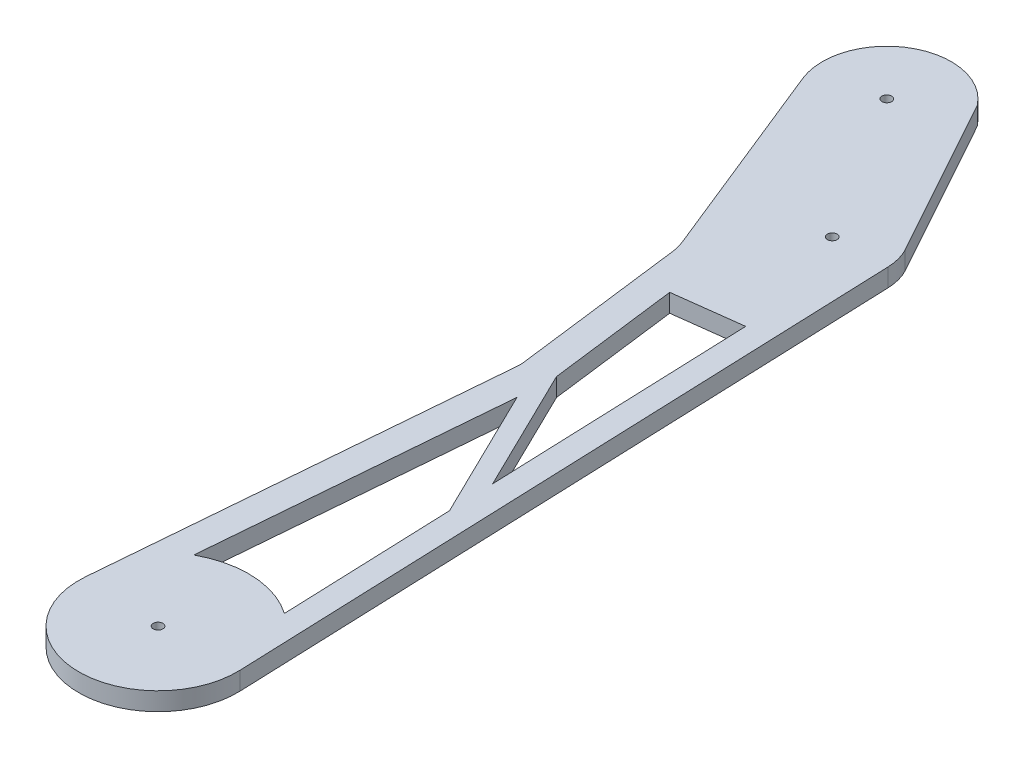
SolidWorks part; units mm, degrees
ref_plane "Front Plane" through (0, 0, 0) normal (0, 0, 1) x (1, 0, 0)
ref_plane "Top Plane" through (0, 0, 0) normal (0, 1, 0) x (1, 0, 0)
ref_plane "Right Plane" through (0, 0, 0) normal (1, 0, 0) x (0, 0, -1)
sketch "Sketch1" plane through (0, 0, 0) normal (0, 1, 0) x (1, 0, 0)
  line L0 (0, 0) -> (0, 63.6789) construction
  line L1 (0, 0) -> (0, 118.022) construction
  line L2 (-7.9677, 70.7448) -> (-13.823, 1.1632)
  line L3 (9.4394, 118.3762) -> (11.1381, 73.1106)
  line L4 (11.1381, 73.1106) -> (13.8621, 0.5202)
  line L5 (-7.2782, 150.7036) -> (8.3679, 122.4044)
  line L6 (-26.6184, 139.4994) -> (-12.3575, 104.1458)
  line L7 (-11.7436, 101.7851) -> (-7.9953, 72.0721)
  line L8 (-2.9552, 72.7079) -> (-5.8163, 95.3881)
  line L9 (-5.8163, 95.3881) -> (5.9914, 96.8777)
  line L10 (-2.9056, 70.3189) -> (-7.6525, 13.9088)
  line L11 (5.9914, 96.8777) -> (9.1397, 12.98)
  line L12 (-2.9552, 72.7079) -> (7.7186, 50.85)
  line L13 (-3.2608, 66.098) -> (8.0127, 43.0122)
  line L14 (8.0127, 43.0122) -> (7.7186, 50.85)
  line L15 (-3.2608, 66.098) -> (-2.9056, 70.3189)
  arc A0 (-13.823, 1.1632) -> (13.8621, 0.5202) centre (0, 0) ccw
  arc A1 (8.3679, 122.4044) -> (9.4394, 118.3762) centre (0, 118.022) cw
  arc A2 (-7.9677, 70.7448) -> (-7.9953, 72.0721) centre (-14.2953, 71.2773) ccw
  circle A3 centre (0, 118.022) radius 0.8509
  arc A4 (-26.6184, 139.4994) -> (-7.2782, 150.7036) centre (-16.1493, 143.7224) cw
  circle A5 centre (-16.1493, 143.7224) radius 0.8509
  arc A6 (-12.3575, 104.1458) -> (-11.7436, 101.7851) centre (-21.1521, 100.5983) cw
  circle A7 centre (0, 0) radius 0.8509
  arc A8 (9.1397, 12.98) -> (-7.6525, 13.9088) centre (0, 0) ccw
  arc A9 (-2.9552, 72.7079) -> (-2.9056, 70.3189) centre (-14.2953, 71.2773) cw
  arc A10 (-2.9056, 70.3189) -> (-2.9552, 72.7079) centre (-14.2953, 71.2773) ccw
  point P9 (0, 82.55)
  point P13 (0, 82.55)
  point P18 (0, 63.5)
  point P20 (0, 101.6)
  point P23 (11.1381, 73.1106)
  point P40 (0, 0)
  point P41 (0, 0)
  point P42 (0, 0)
  point P43 (-7.9677, 14.7019)
  point P44 (0, 0)
  point P45 (0, 0)
  point P46 (0, 0)
  dimension "D1" = 6.35
  dimension "D2" = 1.7018
  dimension "D11" = 1.7018
  dimension "D16" = 11.2887
  dimension "D18" = 9.4831
  dimension "D20" = 1.7018
  dimension "D22" = 15.875
  dimension "D23" = 11.43
  dimension "D3" = 117.856
  dimension "D4" = 72.5904
  dimension "D7" = 82.55
  dimension "D8" = 101.6
  dimension "D9" = 69.5816
  dimension "D10" = 4.81
  dimension "D13" = 30.3531
  dimension "D14" = 32.3365
  dimension "D15" = 206.788
  dimension "D17" = 38.1215
  dimension "D19" = 29.9486
  dimension "D21" = 22.86
  dimension "D25" = 11.9013
  dimension "D26" = 3.175
  dimension "D27" = 210.838
  dimension "D28" = 5.08
  dimension "D29" = 5.08
  dimension "D5" = 173.041
  dimension "D12" = 25.493
  dimension "D24" = 12
extrude "Boss-Extrude3" add sketch "Sketch1" along normal blind 3.175 contours L6 A6 L7 A2 L2 A0 L4 L3 A1 L5 A4 A9 L8 L9 L11 A8 L10 A7 A3 A5 | L12 A9 L10 L13 L11
